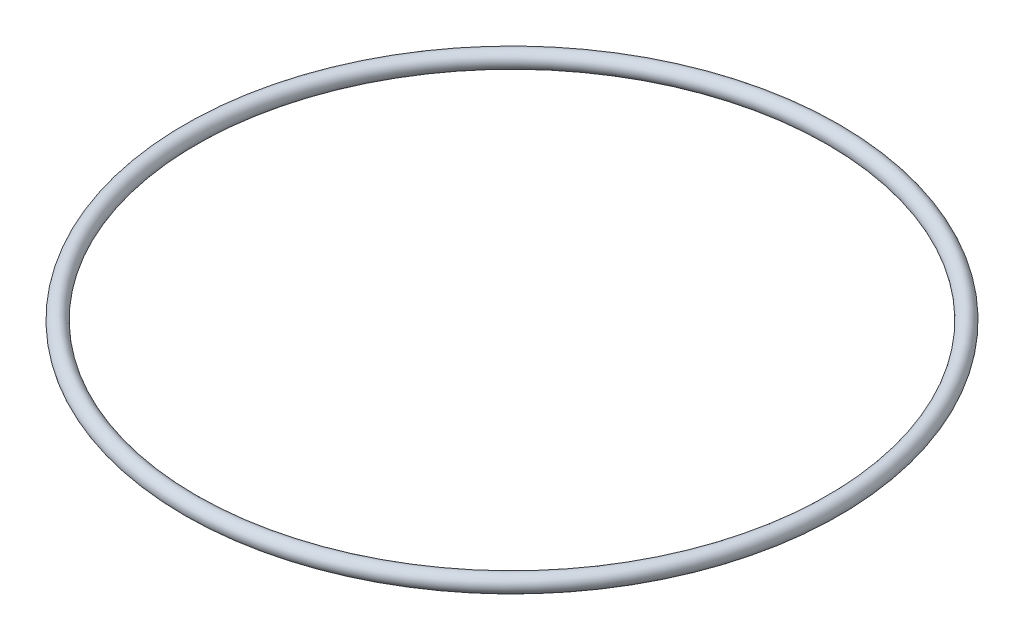
SolidWorks part; units mm, degrees
material "VITON"
ref_plane "Front Plane" through (0, 0, 0) normal (0, 0, 1) x (1, 0, 0)
ref_plane "Top Plane" through (0, 0, 0) normal (0, 1, 0) x (1, 0, 0)
ref_plane "Right Plane" through (0, 0, 0) normal (1, 0, 0) x (0, 0, -1)
sketch "Sketch1" plane through (0, 0, 0) normal (0, 0, 1) x (1, 0, 0)
  line L0 (0, 0) -> (0, 6.5809) construction
  circle A0 centre (-48.87, 0) radius 1.25
  dimension "D1" = 2.5
  dimension "D2" = 48.87
revolve "Revolve1" add sketch "Sketch1" angle 360 about L0
